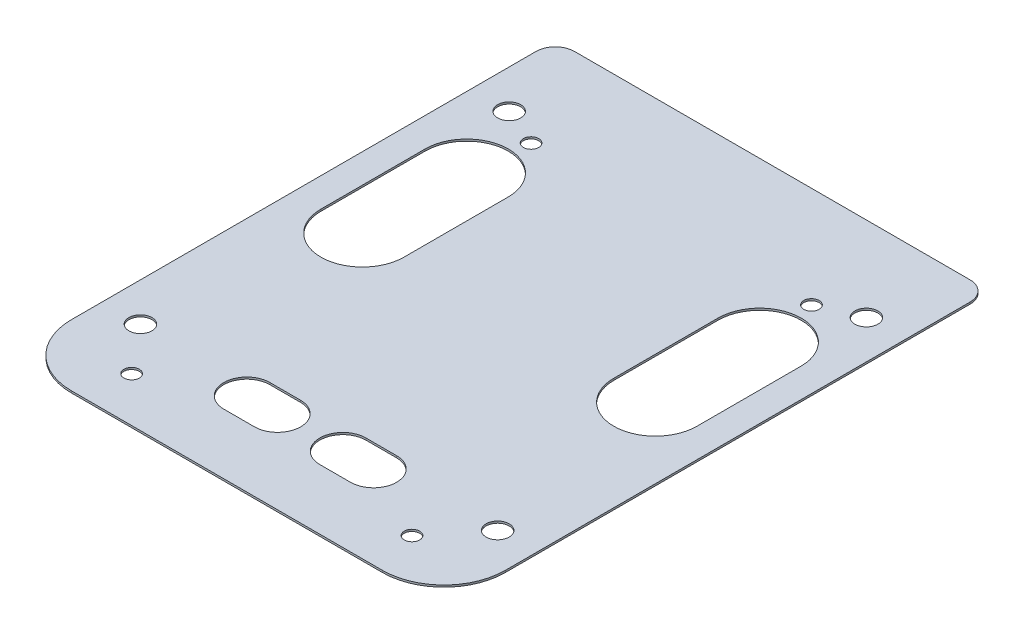
SolidWorks part; units mm, degrees
ref_plane "Front Plane" through (0, 0, 0) normal (0, 0, 1) x (1, 0, 0)
ref_plane "Top Plane" through (0, 0, 0) normal (0, 1, 0) x (1, 0, 0)
ref_plane "Right Plane" through (0, 0, 0) normal (1, 0, 0) x (0, 0, -1)
sketch "Sketch1" plane through (0, 0, 0) normal (0, 1, 0) x (1, 0, 0)
  line L0 (0, 112.7125) -> (0, -112.7125) construction
  line L1 (-81.7562, 112.7125) -> (81.7562, 112.7125)
  line L2 (-89.6937, 104.775) -> (-89.6937, -87.3125)
  line L3 (-64.2937, -112.7125) -> (64.2937, -112.7125)
  line L4 (89.6938, 104.775) -> (89.6938, -87.3125)
  line L5 (-89.6937, 112.7125) -> (89.6938, -112.7125) construction
  line L6 (-89.6937, -112.7125) -> (89.6938, 112.7125) construction
  line L7 (-57.9437, 70.9612) -> (57.9438, 70.9612) construction
  line L8 (-57.9437, 70.9612) -> (-57.9437, -94.1388) construction
  line L9 (-57.9437, -94.1388) -> (57.9438, -94.1388) construction
  line L10 (57.9438, 70.9612) -> (57.9438, -94.1388) construction
  line L11 (-57.9437, 70.9612) -> (57.9438, -94.1388) construction
  line L12 (-57.9437, -94.1388) -> (57.9438, 70.9612) construction
  line L13 (-73.8188, 77.7875) -> (73.8187, 77.7875) construction
  line L14 (-73.8188, 77.7875) -> (-73.8187, -74.6125) construction
  line L15 (-73.8187, -74.6125) -> (73.8188, -74.6125) construction
  line L16 (73.8187, 77.7875) -> (73.8188, -74.6125) construction
  line L17 (-73.8188, 77.7875) -> (73.8188, -74.6125) construction
  line L18 (-73.8187, -74.6125) -> (73.8187, 77.7875) construction
  line L19 (-26.1937, -78.2625) -> (-13.4937, -78.2625) construction
  line L20 (-26.1937, -68.7375) -> (-13.4937, -68.7375)
  line L21 (-26.1937, -87.7875) -> (-13.4937, -87.7875)
  line L22 (26.1938, -78.2625) -> (13.4938, -78.2625) construction
  line L23 (26.1938, -68.7375) -> (13.4938, -68.7375)
  line L24 (26.1938, -87.7875) -> (13.4938, -87.7875)
  line L25 (-60.5295, 46.9468) -> (-60.5295, 3.8557) construction
  line L26 (-43.3464, 46.9468) -> (-43.3464, 3.8557)
  line L27 (-77.7126, 46.9468) -> (-77.7126, 3.8557)
  line L28 (60.5295, 46.9468) -> (60.5295, 3.8557) construction
  line L29 (43.3464, 46.9468) -> (43.3464, 3.8557)
  line L30 (77.7126, 46.9468) -> (77.7126, 3.8557)
  arc A0 (81.7562, 112.7125) -> (89.6938, 104.775) centre (81.7563, 104.775) cw
  arc A1 (-81.7562, 112.7125) -> (-89.6937, 104.775) centre (-81.7562, 104.775) ccw
  arc A2 (64.2937, -112.7125) -> (89.6938, -87.3125) centre (64.2938, -87.3125) ccw
  arc A3 (-89.6937, -87.3125) -> (-64.2937, -112.7125) centre (-64.2937, -87.3125) ccw
  circle A4 centre (-57.9437, 70.9612) radius 3.175
  circle A5 centre (57.9438, 70.9612) radius 3.175
  circle A6 centre (57.9438, -94.1388) radius 3.175
  circle A7 centre (-57.9437, -94.1388) radius 3.175
  circle A8 centre (-73.8187, -74.6125) radius 4.7625
  circle A9 centre (-73.8188, 77.7875) radius 4.7625
  circle A10 centre (73.8187, 77.7875) radius 4.7625
  circle A11 centre (73.8188, -74.6125) radius 4.7625
  arc A12 (-26.1937, -68.7375) -> (-26.1937, -87.7875) centre (-26.1937, -78.2625) ccw
  arc A13 (-13.4937, -87.7875) -> (-13.4937, -68.7375) centre (-13.4937, -78.2625) ccw
  arc A14 (26.1938, -68.7375) -> (26.1938, -87.7875) centre (26.1938, -78.2625) cw
  arc A15 (13.4938, -87.7875) -> (13.4938, -68.7375) centre (13.4938, -78.2625) cw
  arc A16 (-43.3464, 46.9468) -> (-77.7126, 46.9468) centre (-60.5295, 46.9468) ccw
  arc A17 (-77.7126, 3.8557) -> (-43.3464, 3.8557) centre (-60.5295, 3.8557) ccw
  arc A18 (43.3464, 46.9468) -> (77.7126, 46.9468) centre (60.5295, 46.9468) cw
  arc A19 (77.7126, 3.8557) -> (43.3464, 3.8557) centre (60.5295, 3.8557) cw
  point P0 (0, 0)
  point P18 (0, -11.5888)
  point P27 (0, 1.5875)
  point P40 (-19.8437, -78.2625)
  point P47 (19.8438, -78.2625)
  point P54 (-60.5295, 25.4013)
  point P63 (60.5295, 25.4013)
  dimension "D3" = 7.9375
  dimension "D4" = 25.4
  dimension "D8" = 6.35
  dimension "D12" = 9.525
  dimension "D13" = 9.525
  dimension "D16" = 63.5
  dimension "D1" = 179.3875
  dimension "D2" = 225.425
  dimension "D5" = 115.8875
  dimension "D6" = 165.1
  dimension "D7" = 18.5738
  dimension "D9" = 152.4
  dimension "D10" = 147.6375
  dimension "D11" = 38.1
  dimension "D14" = 12.7
  dimension "D15" = 34.45
  dimension "D17" = 11.9812
  dimension "D18" = 34.3662
  dimension "D19" = 43.0911
  dimension "D20" = 116.5682
extrude "Boss-Extrude1" add sketch "Sketch1" along normal blind 0.7937
